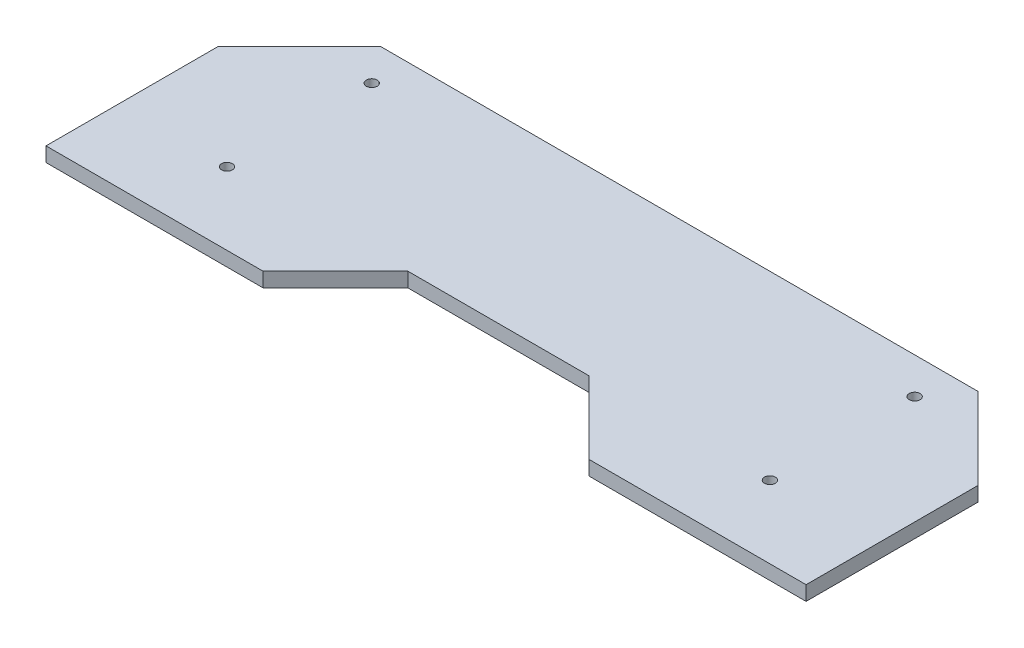
SolidWorks part; units mm, degrees
ref_plane "前视基准面" through (0, 0, 0) normal (0, 0, 1) x (1, 0, 0)
ref_plane "上视基准面" through (0, 0, 0) normal (0, 1, 0) x (1, 0, 0)
ref_plane "右视基准面" through (0, 0, 0) normal (1, 0, 0) x (0, 0, -1)
sketch "草图1" plane through (0, 0, 0) normal (0, 1, 0) x (1, 0, 0)
  line L0 (-67.5, -35) -> (-47.5, -15)
  line L1 (-137.5, -35) -> (-67.5, -35)
  line L2 (-137.5, -35) -> (-137.5, 15)
  line L3 (-117.5, 35) -> (72.5, 35)
  line L4 (92.5, -35) -> (92.5, 15)
  line L5 (22.5, -35) -> (92.5, -35)
  line L6 (-137.5, 15) -> (-117.5, 35)
  line L7 (-22.5, 61.4781) -> (-22.5, -135.1347) construction
  line L8 (92.5, 15) -> (72.5, 35)
  line L9 (-47.5, -15) -> (2.5, -15)
  line L13 (22.5, -35) -> (2.5, -15)
  point P0 (0, 0)
  point P6 (0, -35)
  dimension "D1" = 230
  dimension "D3" = 50
  dimension "D4" = 20
  dimension "D5" = 70
  dimension "D6" = 70
  dimension "D7" = 135
  dimension "D8" = 20
extrude "凸台-拉伸1" add sketch "草图1" along normal blind 4
sketch "草图2" plane through (0, 4, 0) normal (0, 1, 0) x (1, 0, 0)
  line L0 (-137.5, -35) -> (-67.5, -35) construction
  line L1 (-47.5, -15) -> (2.5, -15) construction
  line L2 (-22.5, 54.05) -> (-22.5, -68.4645) construction
  circle A0 centre (-97.5, -15) radius 1.5
  circle A1 centre (-97.5, 25) radius 1.5
  circle A2 centre (52.5, 25) radius 1.5
  circle A3 centre (52.5, -15) radius 1.5
  point P8 (-22.5, -15)
  dimension "D1" = 40
  dimension "D2" = 20
  dimension "D3" = 75
extrude "切除-拉伸1" cut sketch "草图2" against normal blind 4
sketch "草图3" plane through (0, 4, 0) normal (0, 1, 0) x (1, 0, 0)
  line L1 (-137.5, -35) -> (-127.5, -35)
  line L2 (-137.5, -35) -> (-137.5, 34.6789)
  line L3 (-137.5, 34.6789) -> (-127.5, 34.6789)
  line L4 (-127.5, -35) -> (-127.5, 34.6789)
  line L5 (92.5, -35) -> (82.5, -35)
  line L6 (92.5, -35) -> (92.5, 58.0477)
  line L7 (92.5, 58.0477) -> (82.5, 58.0477)
  line L8 (82.5, -35) -> (82.5, 58.0477)
  dimension "D1" = 10
  dimension "D2" = 10
extrude "切除-拉伸2" cut sketch "草图3" against normal blind 4
sketch "草图4" plane through (0, 4, 0) normal (0, 1, 0) x (1, 0, 0)
  line L0 (-127.5, 12.5) -> (-92.1971, 47.8029)
  line L1 (-127.5, -35) -> (-127.5, 25) construction
  line L2 (-92.1971, 47.8029) -> (-150.179, 47.8029)
  line L3 (-150.179, 47.8029) -> (-127.5, 12.5)
  line L4 (82.5, 12.5) -> (37.0053, 57.9947)
  line L5 (82.5, 25) -> (82.5, -35) construction
  line L6 (37.0053, 57.9947) -> (96.5441, 56.2052)
  line L7 (96.5441, 56.2052) -> (82.5, 12.5)
  line L8 (-127.5, -35) -> (-67.5, -35) construction
  line L9 (22.5, -35) -> (82.5, -35) construction
  dimension "D1" = 47.5
  dimension "D2" = 47.5
extrude "切除-拉伸3" cut sketch "草图4" against normal blind 4
